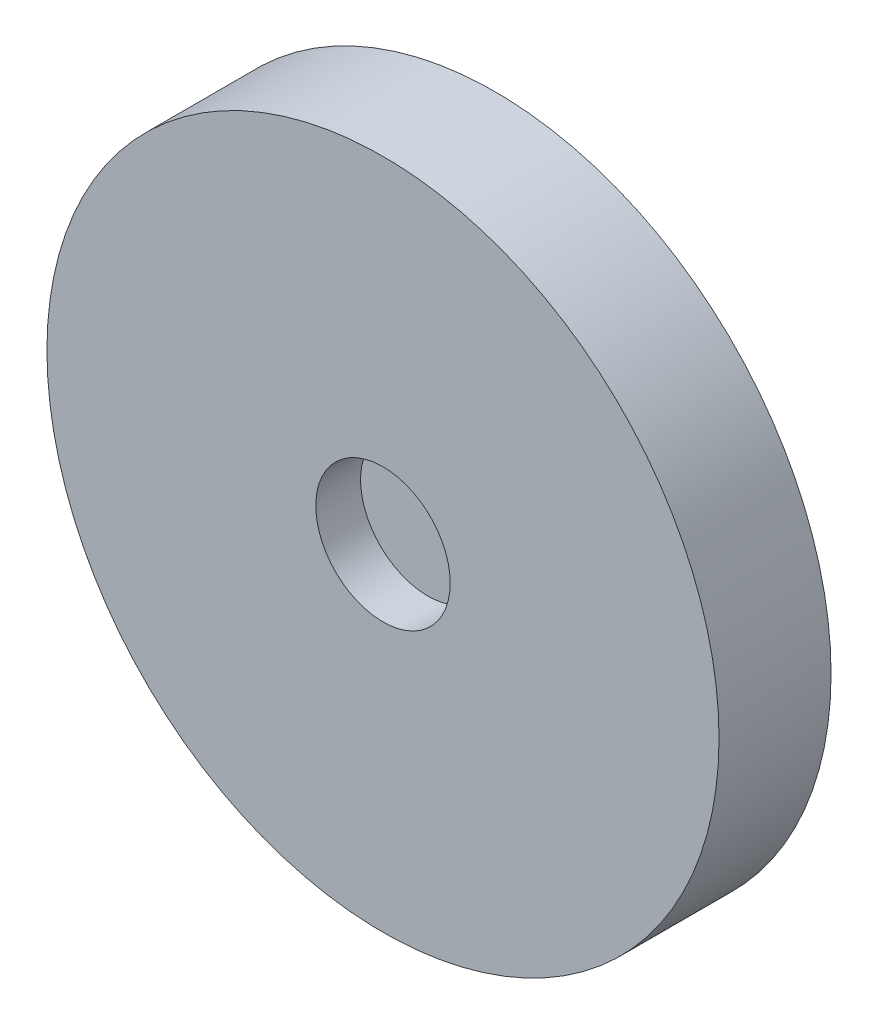
SolidWorks part; units mm, degrees
ref_plane "Alzado" through (0, 0, 0) normal (0, 0, 1) x (1, 0, 0)
ref_plane "Planta" through (0, 0, 0) normal (0, 1, 0) x (1, 0, 0)
ref_plane "Vista lateral" through (0, 0, 0) normal (1, 0, 0) x (0, 0, -1)
sketch "Croquis1" plane through (0, 0, 0) normal (0, 0, 1) x (1, 0, 0)
  circle A0 centre (0, 0) radius 150
  dimension "D1" = 300
extrude "Saliente-Extruir1" add sketch "Croquis1" along normal blind 50
sketch "Croquis2" plane through (0, 0, 50) normal (0, 0, 1) x (1, 0, 0)
  circle A0 centre (0, 0) radius 30
  dimension "D1" = 60
extrude "Cortar-Extruir1" cut sketch "Croquis2" against normal blind 20
